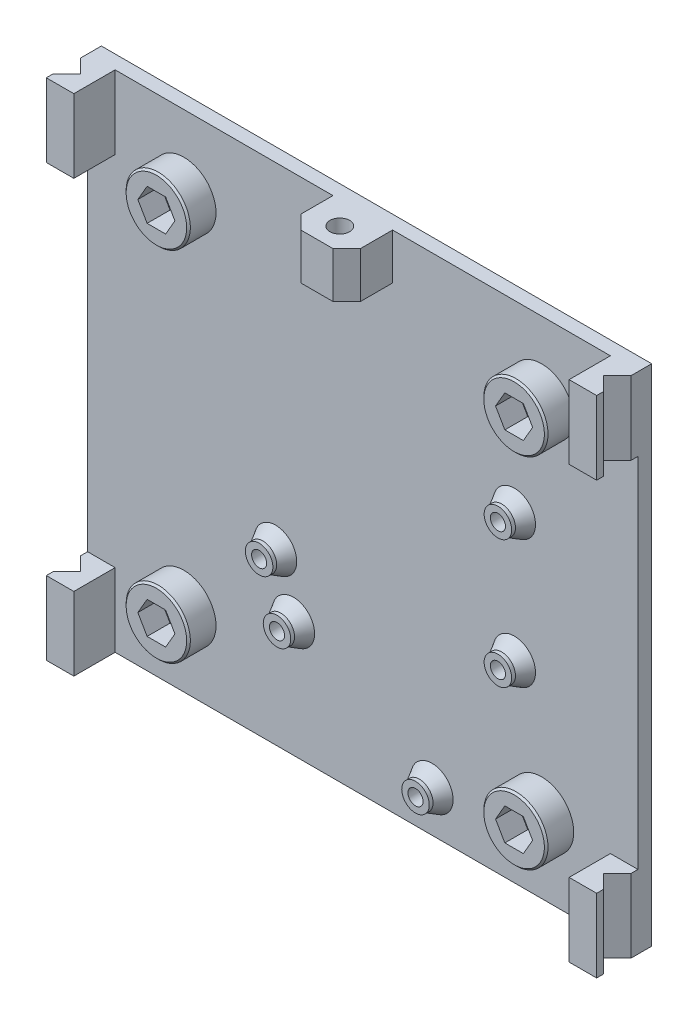
SolidWorks part; units mm, degrees
ref_plane "Front Plane" through (0, 0, 0) normal (0, 0, 1) x (1, 0, 0)
ref_plane "Top Plane" through (0, 0, 0) normal (0, 1, 0) x (1, 0, 0)
ref_plane "Right Plane" through (0, 0, 0) normal (1, 0, 0) x (0, 0, -1)
sketch "Sketch1" plane through (0, 0, 0) normal (0, 0, 1) x (1, 0, 0)
  line L0 (33.07, 14.94) -> (33.07, -13) construction
  line L1 (39, -39) -> (-39, -39) construction
  line L2 (39, -39) -> (39, 39) construction
  line L3 (39, 39) -> (-39, 39) construction
  line L4 (-39, -39) -> (-39, 39) construction
  line L5 (39, -39) -> (-39, 39) construction
  line L6 (39, 39) -> (-39, -39) construction
  line L7 (33.07, -13) -> (-19, -13) construction
  line L8 (-19, -13) -> (-19, -18.08) construction
  line L9 (-15.1, -29.75) -> (-15.1, -46) construction
  line L10 (60, -55) -> (-60, -55)
  line L11 (60, -55) -> (60, 55)
  line L12 (60, 55) -> (-60, 55)
  line L13 (-60, -55) -> (-60, 55)
  line L14 (60, -55) -> (-60, 55) construction
  line L15 (60, 55) -> (-60, -55) construction
  line L16 (-15.1, -46) -> (15.1, -46) construction
  line L17 (0, 0) -> (0, -46) construction
  line L18 (-55, 50) -> (-55, 55) construction
  line L19 (55, -50) -> (-55, -50) construction
  line L20 (55, -50) -> (55, 50) construction
  line L21 (55, 50) -> (-55, 50) construction
  line L22 (-55, -50) -> (-55, 50) construction
  line L23 (55, -50) -> (-55, 50) construction
  line L24 (55, 50) -> (-55, -50) construction
  line L25 (-55, 50) -> (-60, 50) construction
  circle A0 centre (-39, 39) radius 2.15
  circle A1 centre (39, 39) radius 2.15
  circle A2 centre (39, -39) radius 2.15
  circle A3 centre (-39, -39) radius 2.15
  circle A4 centre (33.07, 14.94) radius 1.65
  circle A5 centre (33.07, -13) radius 1.65
  circle A6 centre (-19, -13) radius 1.65 construction
  circle A7 centre (-19, -18.08) radius 1.65
  circle A8 centre (-15.1, -29.75) radius 1.65
  circle A9 centre (15.1, -46) radius 1.65
  circle A10 centre (-55, 50) radius 2.15 construction
  circle A11 centre (55, 50) radius 2.15 construction
  circle A12 centre (55, -50) radius 2.15 construction
  circle A13 centre (-55, -50) radius 2.15 construction
  point P0 (0, 0)
  point P19 (0, 0)
  dimension "D3" = 4.3
  dimension "D7" = 3.3
  dimension "D1" = 78
  dimension "D2" = 78
  dimension "D4" = 27.94
  dimension "D5" = 52.07
  dimension "D6" = 5.08
  dimension "D8" = 110
  dimension "D9" = 120
  dimension "D10" = 30.2
  dimension "D11" = 16.25
  dimension "D12" = 46
  dimension "D13" = 19
  dimension "D14" = 13
  dimension "D15" = 5
extrude "Boss-Extrude1" add sketch "Sketch1" along normal blind 3
sketch "Sketch2" plane through (0, 0, 0) normal (0, 0, -1) x (-1, 0, 0)
  circle A0 centre (-33.07, 14.94) radius 1.65
  circle A1 centre (19, -18.08) radius 1.65
  circle A2 centre (-33.07, -13) radius 1.65
  circle A3 centre (-33.07, -13) radius 3
  circle A4 centre (19, -18.08) radius 3
  circle A5 centre (-33.07, 14.94) radius 3
  circle A6 centre (-33.07, 14.94) radius 1.65 construction
  circle A7 centre (19, -18.08) radius 1.65 construction
  circle A8 centre (-33.07, -13) radius 1.65 construction
  circle A9 centre (15.1, -29.75) radius 1.65
  circle A10 centre (-15.1, -46) radius 1.65
  circle A11 centre (-15.1, -46) radius 3
  circle A12 centre (15.1, -29.75) radius 3
  circle A13 centre (15.1, -29.75) radius 1.65 construction
  circle A14 centre (-15.1, -46) radius 1.65 construction
  dimension "D1" = 6
extrude "Boss-Extrude2" add sketch "Sketch2" against normal blind 6.6
chamfer "Chamfer5" distance 1.6 angle 60 5 edges at (36.07, 14.94, 3) (36.07, -13, 3) (-16, -18.08, 3) (-12.1, -29.75, 3) (18.1, -46, 3)
sketch "Sketch3" plane through (0, 0, 0) normal (0, 0, -1) x (-1, 0, 0)
  line L1 (-31.4823, 12.19) -> (-29.8946, 14.94)
  line L2 (-29.8946, 14.94) -> (-31.4823, 17.69)
  line L3 (-31.4823, 17.69) -> (-34.6577, 17.69)
  line L4 (-34.6577, 17.69) -> (-36.2454, 14.94)
  line L5 (-36.2454, 14.94) -> (-34.6577, 12.19)
  line L6 (-34.6577, 12.19) -> (-31.4823, 12.19)
  line L7 (-31.4823, -15.75) -> (-29.8946, -13)
  line L8 (-29.8946, -13) -> (-31.4823, -10.25)
  line L9 (-31.4823, -10.25) -> (-34.6577, -10.25)
  line L10 (-34.6577, -10.25) -> (-36.2454, -13)
  line L11 (-36.2454, -13) -> (-34.6577, -15.75)
  line L12 (-34.6577, -15.75) -> (-31.4823, -15.75)
  line L13 (20.5877, -20.83) -> (22.1754, -18.08)
  line L14 (22.1754, -18.08) -> (20.5877, -15.33)
  line L15 (20.5877, -15.33) -> (17.4123, -15.33)
  line L16 (17.4123, -15.33) -> (15.8246, -18.08)
  line L17 (15.8246, -18.08) -> (17.4123, -20.83)
  line L18 (17.4123, -20.83) -> (20.5877, -20.83)
  line L19 (16.6877, -32.5) -> (18.2754, -29.75)
  line L20 (18.2754, -29.75) -> (16.6877, -27)
  line L21 (16.6877, -27) -> (13.5123, -27)
  line L22 (13.5123, -27) -> (11.9246, -29.75)
  line L23 (11.9246, -29.75) -> (13.5123, -32.5)
  line L24 (13.5123, -32.5) -> (16.6877, -32.5)
  line L25 (-13.5123, -48.75) -> (-11.9246, -46)
  line L26 (-11.9246, -46) -> (-13.5123, -43.25)
  line L27 (-13.5123, -43.25) -> (-16.6877, -43.25)
  line L28 (-16.6877, -43.25) -> (-18.2754, -46)
  line L29 (-18.2754, -46) -> (-16.6877, -48.75)
  line L30 (-16.6877, -48.75) -> (-13.5123, -48.75)
  circle A0 centre (-33.07, 14.94) radius 2.75 construction
  circle A1 centre (-33.07, -13) radius 2.75 construction
  circle A2 centre (19, -18.08) radius 2.75 construction
  circle A3 centre (15.1, -29.75) radius 2.75 construction
  circle A4 centre (-15.1, -46) radius 2.75 construction
  dimension "D1" = 5.5
extrude "Cut-Extrude1" cut sketch "Sketch3" against normal blind 4
sketch "Sketch4" plane through (0, 0, 0) normal (0, 0, -1) x (-1, 0, 0)
  circle A0 centre (-39, 39) radius 7
  circle A1 centre (-39, 39) radius 2.15
  circle A2 centre (39, 39) radius 7
  circle A3 centre (39, 39) radius 2.15
  circle A4 centre (39, -39) radius 7
  circle A5 centre (39, -39) radius 2.15
  circle A6 centre (-39, -39) radius 7
  circle A7 centre (-39, -39) radius 2.15
  circle A8 centre (-39, 39) radius 2.15 construction
  circle A9 centre (39, 39) radius 2.15 construction
  circle A10 centre (39, -39) radius 2.15 construction
  dimension "D1" = 14
extrude "Boss-Extrude3" add sketch "Sketch4" against normal blind 9
sketch "Sketch5" plane through (0, 0, 9) normal (0, 0, 1) x (1, 0, 0)
  line L1 (-36.9793, 42.5) -> (-41.0207, 42.5)
  line L2 (-41.0207, 42.5) -> (-43.0415, 39)
  line L3 (-43.0415, 39) -> (-41.0207, 35.5)
  line L4 (-41.0207, 35.5) -> (-36.9793, 35.5)
  line L5 (-36.9793, 35.5) -> (-34.9585, 39)
  line L6 (-34.9585, 39) -> (-36.9793, 42.5)
  line L7 (36.9793, 42.5) -> (34.9585, 39)
  line L8 (34.9585, 39) -> (36.9793, 35.5)
  line L9 (36.9793, 35.5) -> (41.0207, 35.5)
  line L10 (41.0207, 35.5) -> (43.0415, 39)
  line L11 (43.0415, 39) -> (41.0207, 42.5)
  line L12 (41.0207, 42.5) -> (36.9793, 42.5)
  line L13 (36.9793, -35.5) -> (34.9585, -39)
  line L14 (34.9585, -39) -> (36.9793, -42.5)
  line L15 (36.9793, -42.5) -> (41.0207, -42.5)
  line L16 (41.0207, -42.5) -> (43.0415, -39)
  line L17 (43.0415, -39) -> (41.0207, -35.5)
  line L18 (41.0207, -35.5) -> (36.9793, -35.5)
  line L19 (-36.9793, -35.5) -> (-41.0207, -35.5)
  line L20 (-41.0207, -35.5) -> (-43.0415, -39)
  line L21 (-43.0415, -39) -> (-41.0207, -42.5)
  line L22 (-41.0207, -42.5) -> (-36.9793, -42.5)
  line L23 (-36.9793, -42.5) -> (-34.9585, -39)
  line L24 (-34.9585, -39) -> (-36.9793, -35.5)
  circle A0 centre (-39, 39) radius 3.5 construction
  circle A1 centre (39, 39) radius 3.5 construction
  circle A2 centre (39, -39) radius 3.5 construction
  circle A3 centre (-39, -39) radius 3.5 construction
  dimension "D1" = 7
extrude "Cut-Extrude2" cut sketch "Sketch5" against normal blind 5
chamfer "Chamfer2" distance 0.4 angle 45 4 edges at (-46, -39, 9) (32, -39, 9) (32, 39, 9) (-46, 39, 9)
sketch "Sketch6" plane through (-60, 0, 0) normal (-1, 0, 0) x (0, 0, 1)
  line L1 (3, 55) -> (12, 55)
  line L2 (3, 55) -> (3, 39)
  line L3 (3, 39) -> (12, 39)
  line L4 (12, 55) -> (12, 39)
  line L5 (0, 55) -> (0, -55) construction
  line L6 (3, -55) -> (12, -55)
  line L7 (3, -55) -> (3, -39)
  line L8 (3, -39) -> (12, -39)
  line L9 (12, -55) -> (12, -39)
  dimension "D1" = 12
  dimension "D2" = 16
extrude "Boss-Extrude4" add sketch "Sketch6" against normal blind 6
mirror "Mirror1" about plane through (0, 0, 0) normal (1, 0, 0) of "Boss-Extrude4"
sketch "Sketch7" plane through (0, 55, 0) normal (0, 1, 0) x (1, 0, 0)
  line L0 (-60, -10.5) -> (-57, -7.5)
  line L1 (-60, -12) -> (-60, 0) construction
  line L2 (-57, -7.5) -> (-60, -4.5)
  line L3 (-60, -4.5) -> (-60, -10.5)
  line L4 (60, -10.5) -> (57, -7.5)
  line L5 (60, -12) -> (60, 0) construction
  line L6 (57, -7.5) -> (60, -4.5)
  line L7 (-54, -12) -> (-54, -3) construction
  line L8 (-57, -7.5) -> (-54, -7.5) construction
  line L9 (-54, -7.5) -> (57, -7.5) construction
  line L10 (60, -4.5) -> (60, -10.5)
  line L11 (60, -4.5) -> (-60, -4.5) construction
  dimension "D1" = 6
extrude "Cut-Extrude3" cut sketch "Sketch7" against normal through all both
sketch "Sketch8" plane through (0, 55, 0) normal (0, 1, 0) x (1, 0, 0)
  line L0 (54, -3) -> (-54, -3) construction
  line L1 (6.5, -13) -> (-6.5, -13)
  line L2 (6.5, -13) -> (6.5, -3)
  line L3 (6.5, -3) -> (-6.5, -3)
  line L4 (-6.5, -13) -> (-6.5, -3)
  line L5 (6.5, -13) -> (-6.5, -3) construction
  line L6 (6.5, -3) -> (-6.5, -13) construction
  line L7 (0, 0) -> (0, -8) construction
  line L8 (6.5, -13) -> (6.5, 0) construction
  line L9 (60, 0) -> (-60, 0) construction
  circle A0 centre (0, -8) radius 2.15
  point P0 (0, -8)
  dimension "D2" = 4.3
  dimension "D1" = 13
extrude "Boss-Extrude5" add sketch "Sketch8" against normal blind 10
sketch "Sketch9" plane through (0, 45, 0) normal (0, -1, 0) x (1, 0, 0)
  line L1 (0, 12.0415) -> (-3.5, 10.0207)
  line L2 (-3.5, 10.0207) -> (-3.5, 5.9793)
  line L3 (-3.5, 5.9793) -> (0, 3.9585)
  line L4 (0, 3.9585) -> (3.5, 5.9793)
  line L5 (3.5, 5.9793) -> (3.5, 10.0207)
  line L6 (3.5, 10.0207) -> (0, 12.0415)
  circle A0 centre (0, 8) radius 3.5 construction
  dimension "D1" = 7
extrude "Cut-Extrude5" cut sketch "Sketch9" against normal blind 5
chamfer "Chamfer9" distance 3 angle 45 2 edges at (6.5, 50, 13) (-6.5, 50, 13)
ref_plane "Plane1" through (0, 0, 7.5) normal (0, 0, 1) x (1, 0, 0)
